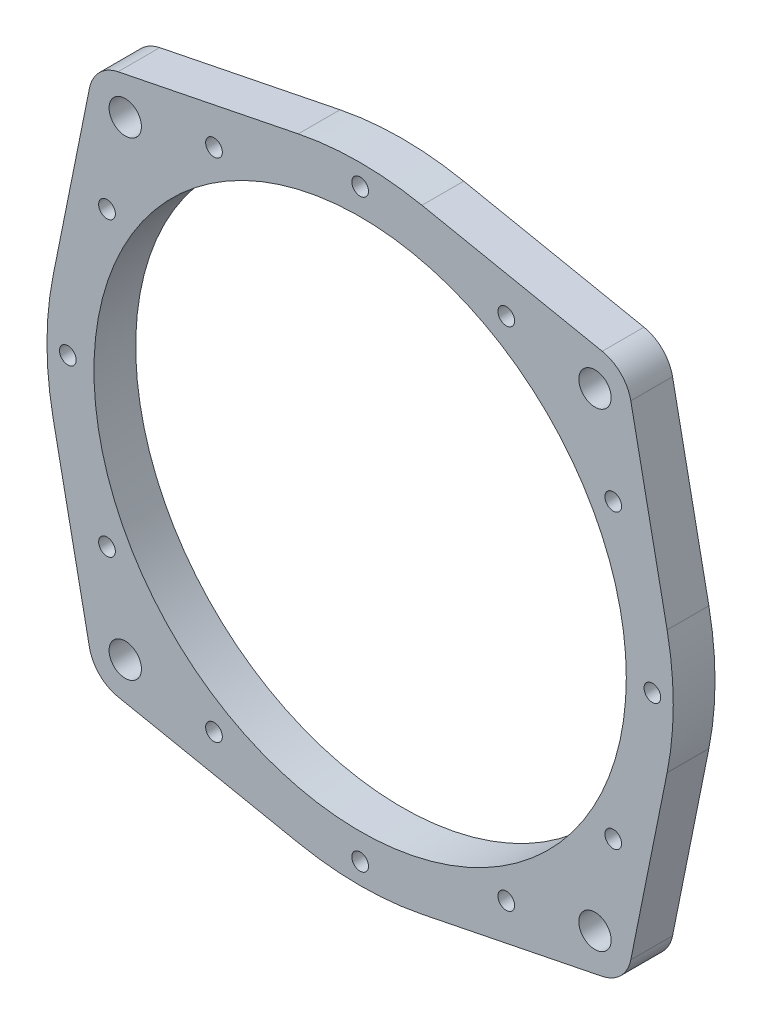
SolidWorks part; units mm, degrees
material "1060 合金"
ref_plane "前视基准面" through (0, 0, 0) normal (0, 0, 1) x (1, 0, 0)
ref_plane "上视基准面" through (0, 0, 0) normal (0, 1, 0) x (1, 0, 0)
ref_plane "右视基准面" through (0, 0, 0) normal (1, 0, 0) x (0, 0, -1)
sketch "草图1" plane through (0, 0, 0) normal (0, 0, 1) x (1, 0, 0)
  line L0 (-51.8622, 46.3823) -> (-58.8186, 11.8481)
  line L1 (45, -45) -> (-45, -45) construction
  line L2 (45, -45) -> (45, 45) construction
  line L3 (45, 45) -> (-45, 45) construction
  line L4 (-45, -45) -> (-45, 45) construction
  line L5 (45, -45) -> (-45, 45) construction
  line L6 (45, 45) -> (-45, -45) construction
  line L7 (-58.8186, -11.8481) -> (-51.8622, -46.3823)
  line L8 (-46.3823, -51.8622) -> (-11.8481, -58.8186)
  line L9 (11.8481, -58.8186) -> (46.3823, -51.8622)
  line L10 (51.8622, -46.3823) -> (58.8186, -11.8481)
  line L11 (58.8186, 11.8481) -> (51.8622, 46.3823)
  line L12 (46.3823, 51.8622) -> (11.8481, 58.8186)
  line L13 (-11.8481, 58.8186) -> (-46.3823, 51.8622)
  circle A0 centre (45, 45) radius 3.1
  circle A1 centre (-45, 45) radius 3.1
  circle A2 centre (-45, -45) radius 3.1
  circle A3 centre (45, -45) radius 3.1
  circle A4 centre (0, 0) radius 56 construction
  circle A5 centre (0, 56) radius 1.6
  circle A6 centre (28, 48.4974) radius 1.6
  circle A7 centre (48.4974, 28) radius 1.6
  circle A8 centre (56, 0) radius 1.6
  circle A9 centre (48.4974, -28) radius 1.6
  circle A10 centre (28, -48.4974) radius 1.6
  circle A11 centre (0, -56) radius 1.6
  circle A12 centre (-28, -48.4974) radius 1.6
  circle A13 centre (-48.4974, -28) radius 1.6
  circle A14 centre (-56, 0) radius 1.6
  circle A15 centre (-48.4974, 28) radius 1.6
  circle A16 centre (-28, 48.4974) radius 1.6
  arc A17 (-11.8481, -58.8186) -> (11.8481, -58.8186) centre (0, 0) ccw
  arc A18 (-58.8186, 11.8481) -> (-58.8186, -11.8481) centre (0, 0) ccw
  arc A19 (11.8481, 58.8186) -> (-11.8481, 58.8186) centre (0, 0) ccw
  arc A20 (58.8186, -11.8481) -> (58.8186, 11.8481) centre (0, 0) ccw
  arc A21 (-51.8622, 46.3823) -> (-46.3823, 51.8622) centre (-45, 45) cw
  arc A22 (51.8622, 46.3823) -> (46.3823, 51.8622) centre (45, 45) ccw
  arc A23 (46.3823, -51.8622) -> (51.8622, -46.3823) centre (45, -45) ccw
  arc A24 (-51.8622, -46.3823) -> (-46.3823, -51.8622) centre (-45, -45) ccw
  circle A26 centre (0, 0) radius 51
  point P0 (0, 0)
  point P38 (0, 0)
  dimension "D1" = 90
  dimension "D2" = 6.2
  dimension "D3" = 112
  dimension "D4" = 3.2
  dimension "D6" = 60
  dimension "D7" = 7
  dimension "D8" = 102
  dimension "D5" = 12
extrude "凸台-拉伸1" add sketch "草图1" along normal blind 8
sketch "草图2" plane through (0, 0, 0) normal (0, 0, -1) x (-1, 0, 0)
  circle A0 centre (-28, 48.4974) radius 2.6
  circle A1 centre (0, 56) radius 2.6
  circle A2 centre (28, 48.4974) radius 2.6
  circle A3 centre (48.4974, 28) radius 2.6
  circle A4 centre (56, 0) radius 2.6
  circle A5 centre (48.4974, -28) radius 2.6
  circle A6 centre (28, -48.4974) radius 2.6
  circle A7 centre (0, -56) radius 2.6
  circle A8 centre (-28, -48.4974) radius 2.6
  circle A9 centre (-48.4974, -28) radius 2.6
  circle A10 centre (-56, 0) radius 2.6
  circle A11 centre (-48.4974, 28) radius 2.6
  dimension "D1" = 5.2
  dimension "D2" = 12
extrude "切除-拉伸1" cut sketch "草图2" against normal blind 4
